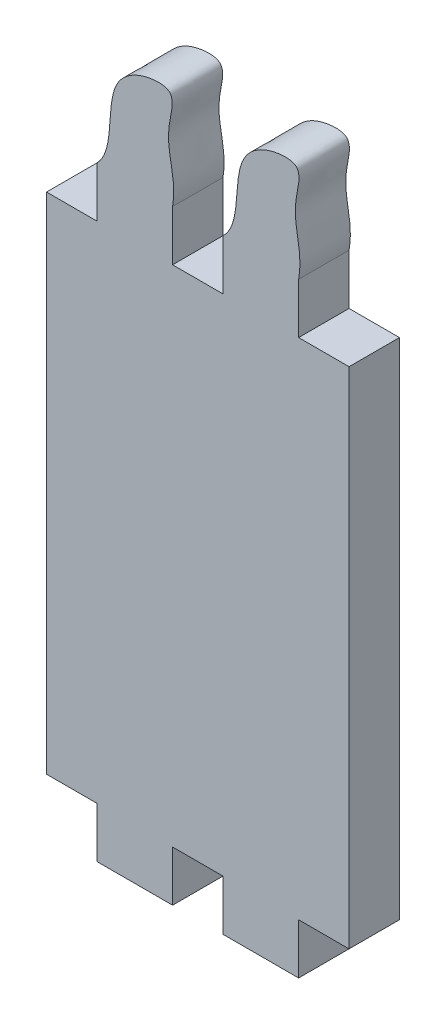
SolidWorks part; units mm, degrees
ref_plane "Front Plane" through (0, 0, 0) normal (0, 0, 1) x (1, 0, 0)
ref_plane "Top Plane" through (0, 0, 0) normal (0, 1, 0) x (1, 0, 0)
ref_plane "Right Plane" through (0, 0, 0) normal (1, 0, 0) x (0, 0, -1)
sketch "Sketch1" plane through (0, 0, 0) normal (0, 0, 1) x (1, 0, 0)
  line L0 (0, 0) -> (-3.2347, 0)
  line L1 (9.525, -15.875) -> (-9.525, -15.875)
  line L2 (9.525, -15.875) -> (9.525, 15.875)
  line L3 (9.525, 15.875) -> (-9.525, 15.875)
  line L4 (-9.525, -15.875) -> (-9.525, 15.875)
  line L5 (9.525, -15.875) -> (-9.525, 15.875) construction
  line L6 (9.525, 15.875) -> (-9.525, -15.875) construction
  line L7 (6.35, -15.875) -> (6.35, -19.05)
  line L8 (-6.35, 15.875) -> (-1.5875, 15.875)
  line L9 (-6.35, 15.875) -> (-6.35, 19.05)
  line L10 (-6.35, 19.05) -> (-1.5875, 19.05)
  line L11 (-1.5875, 15.875) -> (-1.5875, 19.05)
  line L12 (1.5875, 15.875) -> (6.35, 15.875)
  line L13 (1.5875, 15.875) -> (1.5875, 19.05)
  line L14 (1.5875, 19.05) -> (6.35, 19.05)
  line L15 (6.35, 15.875) -> (6.35, 19.05)
  line L16 (1.5875, -15.875) -> (1.5875, -19.05)
  line L17 (1.5875, -19.05) -> (6.35, -19.05)
  line L18 (-6.35, -15.875) -> (-6.35, -19.05)
  line L19 (-6.35, -19.05) -> (-1.5875, -19.05)
  line L20 (-1.5875, -15.875) -> (-1.5875, -19.05)
  circle A0 centre (-19.05, 0) radius 2.3813
  circle A1 centre (-19.05, 0) radius 6.35
  spline S0 degree 3 poles (-21.5476, 5.8382) (-17.7414, 7.4665) (-15.0309, 8.8365) (-13.0093, 15.9171) (-9.525, 15.875) knots 0 0 0 0 0.458191 1 1 1 1
  spline S1 degree 3 poles (-6.35, 19.05) (-5.1089, 20.3128) (-6.2488, 23.7826) (-3.5047, 25.4227) (-1.2706, 25.4019) (-2.3305, 22.1182) (-1.303, 20.9023) (-1.5875, 19.05) knots 0 0 0 0 0.348301 0.511854 0.587996 0.709542 1 1 1 1
  spline S2 degree 3 poles (1.5875, 19.05) (2.8761, 20.283) (1.7509, 23.717) (4.4801, 25.3439) (6.714, 25.3233) (5.6646, 22.0756) (6.6616, 20.8588) (6.35, 19.05) knots 0 0 0 0 0.347504 0.512636 0.589513 0.712232 1 1 1 1
  spline S3 degree 3 poles (-21.5476, -5.8382) (-17.7414, -7.4665) (-15.0309, -8.8365) (-13.0093, -15.9171) (-9.525, -15.875) knots 0 0 0 0 0.458191 1 1 1 1
  point P0 (0, 0)
  dimension "D3" = 4.7625
  dimension "D4" = 9.525
  dimension "D5" = 12.7
  dimension "D1" = 19.05
  dimension "D2" = 31.75
  dimension "D6" = 4.7625
  dimension "D7" = 4.7625
  dimension "D8" = 3.175
  dimension "D9" = 3.175
  dimension "D10" = 3.175
  dimension "D11" = 3.175
extrude "Boss-Extrude1" add sketch "Sketch1" along normal blind 3.175
sketch "Sketch2" plane through (0, 0, 3.175) normal (0, 0, 1) x (1, 0, 0)
  line L0 (-6.35, 15.875) -> (-6.35, 19.05) construction
  line L1 (-27.6789, 16.8856) -> (-9.525, 16.8856)
  line L2 (-27.6789, 16.8856) -> (-27.6789, -19.661)
  line L3 (-27.6789, -19.661) -> (-9.525, -19.661)
  line L4 (-9.525, 16.8856) -> (-9.525, -19.661)
  dimension "D1" = 3.175
extrude "Cut-Extrude1" cut sketch "Sketch2" against normal through all
